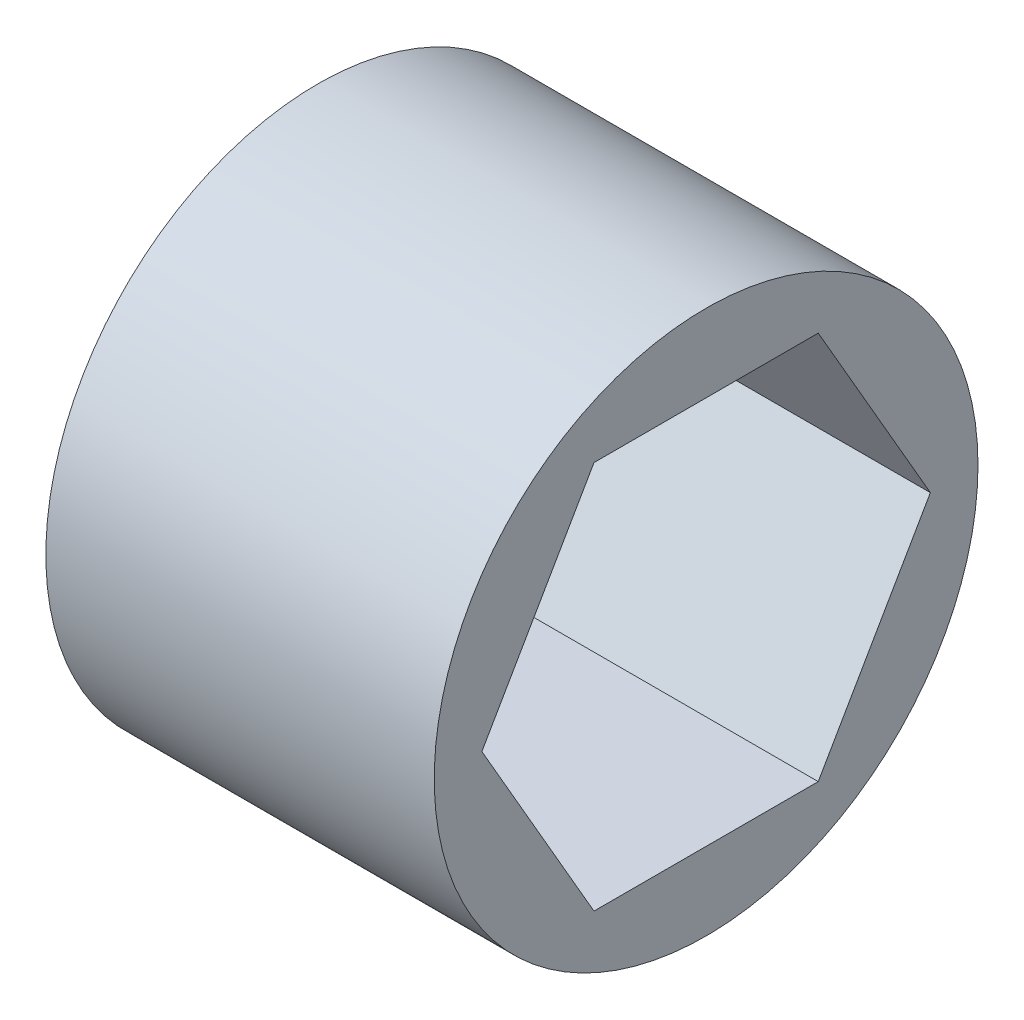
SolidWorks part; units mm, degrees
material "Nylon 6/10"
ref_plane "Front Plane" through (0, 0, 0) normal (0, 0, 1) x (1, 0, 0)
ref_plane "Top Plane" through (0, 0, 0) normal (0, 1, 0) x (1, 0, 0)
ref_plane "Right Plane" through (0, 0, 0) normal (1, 0, 0) x (0, 0, -1)
sketch "Sketch1" plane through (0, 0, 0) normal (1, 0, 0) x (0, 0, -1)
  line L1 (-3.6662, 6.35) -> (-7.3323, 0)
  line L2 (-7.3323, 0) -> (-3.6662, -6.35)
  line L3 (-3.6662, -6.35) -> (3.6662, -6.35)
  line L4 (3.6662, -6.35) -> (7.3323, 0)
  line L5 (7.3323, 0) -> (3.6662, 6.35)
  line L6 (3.6662, 6.35) -> (-3.6662, 6.35)
  circle A0 centre (0, 0) radius 6.35 construction
  circle A1 centre (0, 0) radius 8.89
  dimension "D2" = 17.78
  dimension "D1" = 12.7
sketch "Sketch2" [suppressed] plane through (0, 0, 0) normal (1, 0, 0) x (0, 0, -1)
  line L0 (-3.6662, 6.35) -> (-7.3323, 0) construction
  line L1 (-7.3323, 0) -> (-3.6662, -6.35) construction
  line L2 (-3.6662, -6.35) -> (3.6662, -6.35) construction
  line L3 (3.6662, -6.35) -> (7.3323, 0) construction
  line L4 (7.3323, 0) -> (3.6662, 6.35) construction
  line L5 (3.6662, 6.35) -> (-3.6662, 6.35) construction
  line L6 (-3.6662, 6.35) -> (-7.3323, 0)
  line L7 (-7.3323, 0) -> (-3.6662, -6.35)
  line L8 (-3.6662, -6.35) -> (3.6662, -6.35)
  line L9 (3.6662, -6.35) -> (7.3323, 0)
  line L10 (7.3323, 0) -> (3.6662, 6.35)
  line L11 (3.6662, 6.35) -> (-3.6662, 6.35)
  circle A0 centre (0, 0) radius 8.89 construction
  circle A1 centre (0, 0) radius 8.89
extrude "Boss-Extrude1" [suppressed] add sketch "Sketch2" along normal blind 3.175
sketch "Sketch3" [suppressed] plane through (0, 0, 0) normal (1, 0, 0) x (0, 0, -1)
  line L0 (3.6662, 6.35) -> (-3.6662, 6.35) construction
  line L1 (-3.6662, 6.35) -> (-7.3323, 0) construction
  line L2 (-7.3323, 0) -> (-3.6662, -6.35) construction
  line L3 (-3.6662, -6.35) -> (3.6662, -6.35) construction
  line L4 (3.6662, -6.35) -> (7.3323, 0) construction
  line L5 (7.3323, 0) -> (3.6662, 6.35) construction
  line L6 (3.6662, 6.35) -> (-3.6662, 6.35)
  line L7 (-3.6662, 6.35) -> (-7.3323, 0)
  line L8 (-7.3323, 0) -> (-3.6662, -6.35)
  line L9 (-3.6662, -6.35) -> (3.6662, -6.35)
  line L10 (3.6662, -6.35) -> (7.3323, 0)
  line L11 (7.3323, 0) -> (3.6662, 6.35)
  circle A0 centre (0, 0) radius 8.89 construction
  circle A1 centre (0, 0) radius 8.89
extrude "Boss-Extrude2" [suppressed] add sketch "Sketch3" along normal blind 6.35
sketch "Sketch4" plane through (0, 0, 0) normal (1, 0, 0) x (0, 0, -1)
  line L0 (3.6662, 6.35) -> (-3.6662, 6.35) construction
  line L1 (-3.6662, 6.35) -> (-7.3323, 0) construction
  line L2 (-7.3323, 0) -> (-3.6662, -6.35) construction
  line L3 (-3.6662, -6.35) -> (3.6662, -6.35) construction
  line L4 (3.6662, -6.35) -> (7.3323, 0) construction
  line L5 (7.3323, 0) -> (3.6662, 6.35) construction
  line L6 (3.6662, 6.35) -> (-3.6662, 6.35)
  line L7 (-3.6662, 6.35) -> (-7.3323, 0)
  line L8 (-7.3323, 0) -> (-3.6662, -6.35)
  line L9 (-3.6662, -6.35) -> (3.6662, -6.35)
  line L10 (3.6662, -6.35) -> (7.3323, 0)
  line L11 (7.3323, 0) -> (3.6662, 6.35)
  circle A0 centre (0, 0) radius 8.89 construction
  circle A1 centre (0, 0) radius 8.89
extrude "Boss-Extrude3" add sketch "Sketch4" along normal blind 12.7
